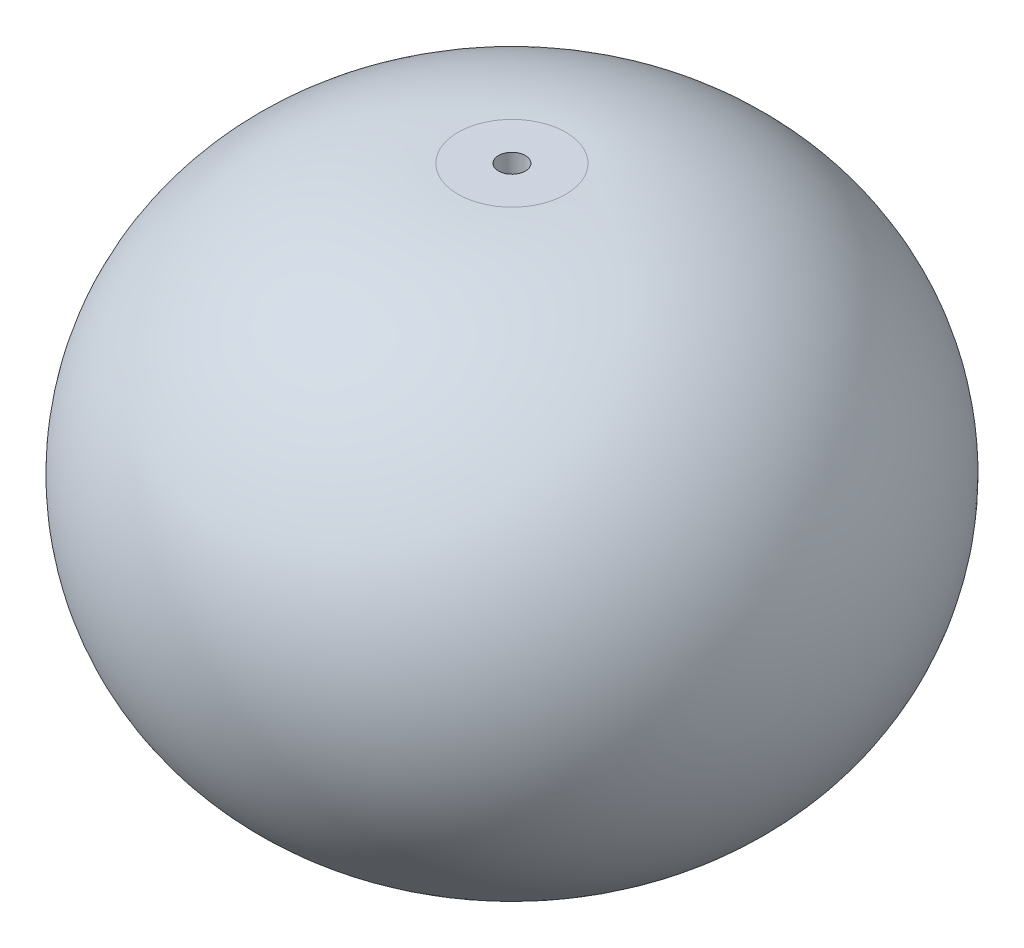
SolidWorks part; units mm, degrees
ref_plane "Front Plane" through (0, 0, 0) normal (0, 0, 1) x (1, 0, 0)
ref_plane "Top Plane" through (0, 0, 0) normal (0, 1, 0) x (1, 0, 0)
ref_plane "Right Plane" through (0, 0, 0) normal (1, 0, 0) x (0, 0, -1)
sketch "Sketch4" plane through (0, 0, 0) normal (0, 0, 1) x (1, 0, 0)
  line L0 (0, 0) -> (62.23, 0)
  line L1 (0, 0) -> (0, 50.8)
  line L2 (0, 50.8) -> (10.16, 50.8)
  line L3 (0, 0) -> (10.16, 0)
  ellipse E0 centre (10.16, 0) end of major axis (-41.91, 0) minor radius 50.8 (62.23, 0) -> (10.16, 50.8) ccw
revolve "Revolve1" add sketch "Sketch4" angle 360 about L1
sketch "Sketch5" plane through (0, 0, 0) normal (0, -1, 0) x (1, 0, 0)
  circle A0 centre (0, 0) radius 6.985
extrude "Cut-Extrude1" cut sketch "Sketch5" against normal blind 38.1
sketch "Sketch6" plane through (0, 38.1, 0) normal (0, -1, 0) x (1, 0, 0)
  circle A0 centre (0, 0) radius 2.54
extrude "Cut-Extrude2" cut sketch "Sketch6" against normal blind 38.1
mirror "Mirror1" of "Cut-Extrude1", "Revolve1", "Cut-Extrude2"
